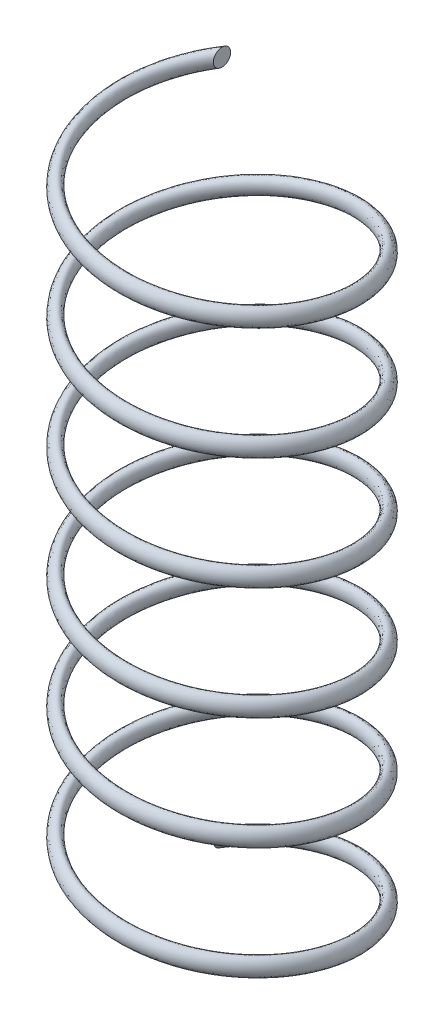
SolidWorks part; units mm, degrees
ref_plane "Plan de face" through (0, 0, 0) normal (0, 0, 1) x (1, 0, 0)
ref_plane "Plan de dessus" through (0, 0, 0) normal (0, 1, 0) x (1, 0, 0)
ref_plane "Plan de droite" through (0, 0, 0) normal (1, 0, 0) x (0, 0, -1)
sketch "Esquisse1" plane through (0, 0, 0) normal (0, 1, 0) x (1, 0, 0)
  circle A0 centre (0, 0) radius 3.4
  dimension "D1" = 6.8
curve "Hélice/Spirale2" pitch 3.25 height 19.5 turns 6
ref_plane "Plan1" through (-2.4042, 0, 0) normal (1, 0, 0) x (0, 0, -1)
sketch "Esquisse5" plane through (-2.4042, 0, 0) normal (1, 0, 0) x (0, 0, -1)
  circle A0 centre (2.4042, 0) radius 0.25
  spline S0 degree 3 poles (2.4042, 0) (2.7169, 0.0673) (3.2239, 0.2033) (3.4883, 0.4062) (3.223, 0.6094) (2.4667, 0.8125) (1.335, 1.0156) (0, 1.2187) (-1.335, 1.4219) (-2.4668, 1.625) (-3.223, 1.8281) (-3.4885, 2.0312) (-3.223, 2.2344) (-2.4668, 2.4375) (-0.9577, 2.7083) (0.9577, 2.9792) (2.4668, 3.25) (3.223, 3.4531) (3.4885, 3.6562) (3.223, 3.8594) (2.4668, 4.0625) (0.9577, 4.3333) (-0.9577, 4.6042) (-2.4668, 4.875) (-3.223, 5.0781) (-3.4885, 5.2813) (-3.223, 5.4844) (-2.4668, 5.6875) (-0.9577, 5.9583) (0.9577, 6.2292) (2.4668, 6.5) (3.223, 6.7031) (3.4885, 6.9063) (3.223, 7.1094) (2.4668, 7.3125) (0.9577, 7.5833) (-0.9577, 7.8542) (-2.4668, 8.125) (-3.223, 8.3281) (-3.4885, 8.5313) (-3.223, 8.7344) (-2.4668, 8.9375) (-0.9577, 9.2083) (0.9577, 9.4792) (2.4668, 9.75) (3.223, 9.9531) (3.4885, 10.1563) (3.223, 10.3594) (2.4668, 10.5625) (0.9577, 10.8333) (-0.9577, 11.1042) (-2.4668, 11.375) (-3.223, 11.5781) (-3.4885, 11.7813) (-3.223, 11.9844) (-2.4668, 12.1875) (-0.9577, 12.4583) (0.9577, 12.7292) (2.4668, 13) (3.223, 13.2031) (3.4885, 13.4063) (3.223, 13.6094) (2.4668, 13.8125) (0.9577, 14.0833) (-0.9577, 14.3542) (-2.4668, 14.625) (-3.223, 14.8281) (-3.4885, 15.0313) (-3.223, 15.2344) (-2.4668, 15.4375) (-0.9577, 15.7083) (0.9577, 15.9792) (2.4668, 16.25) (3.223, 16.4531) (3.4885, 16.6563) (3.223, 16.8594) (2.4668, 17.0625) (0.9577, 17.3333) (-0.9577, 17.6042) (-2.4668, 17.875) (-3.223, 18.0781) (-3.4885, 18.2813) (-3.223, 18.4844) (-2.4667, 18.6875) (-1.3351, 18.8906) (0.0002, 19.0938) (1.3341, 19.2967) (2.0914, 19.4327) (2.4042, 19.5) knots 0 0 0 0 0.010417 0.020833 0.03125 0.041667 0.052083 0.0625 0.072917 0.083333 0.09375 0.104167 0.114583 0.125 0.135417 0.15625 0.166667 0.177083 0.1875 0.197917 0.208333 0.21875 0.239583 0.25 0.260417 0.270833 0.28125 0.291667 0.302083 0.322917 0.333333 0.34375 0.354167 0.364583 0.375 0.385417 0.40625 0.416667 0.427083 0.4375 0.447917 0.458333 0.46875 0.489583 0.5 0.510417 0.520833 0.53125 0.541667 0.552083 0.572917 0.583333 0.59375 0.604167 0.614583 0.625 0.635417 0.65625 0.666667 0.677083 0.6875 0.697917 0.708333 0.71875 0.739583 0.75 0.760417 0.770833 0.78125 0.791667 0.802083 0.822917 0.833333 0.84375 0.854167 0.864583 0.875 0.885417 0.90625 0.916667 0.927083 0.9375 0.947917 0.958333 0.96875 0.979167 0.989583 1 1 1 1 construction
  dimension "D1" = 0.5
sweep "Balayage1" add profiles "Esquisse5" path "Hélice/Spirale2"
